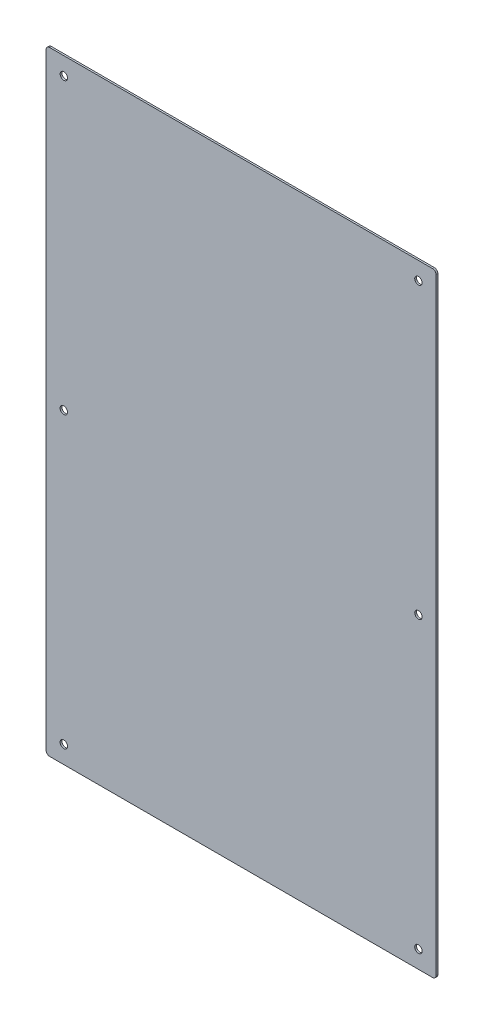
SolidWorks part; units mm, degrees
ref_plane "Спереди" through (0, 0, 0) normal (0, 0, 1) x (1, 0, 0)
ref_plane "Сверху" through (0, 0, 0) normal (0, 1, 0) x (1, 0, 0)
ref_plane "Справа" through (0, 0, 0) normal (1, 0, 0) x (0, 0, -1)
sketch "Эскиз1" plane through (0, 0, 0) normal (0, 0, 1) x (1, 0, 0)
  line L1 (0, -29.1001) -> (0, 23.6764) construction
  line L3 (-108.5, -174) -> (108.5, -174)
  line L4 (-110.5, -172) -> (-110.5, 172)
  line L5 (-108.5, 174) -> (108.5, 174)
  line L6 (110.5, -172) -> (110.5, 172)
  circle A0 centre (-100.5, 164) radius 2.1
  circle A1 centre (-100.5, 0) radius 2.1
  circle A2 centre (-100.5, -164) radius 2.1
  circle A3 centre (100.5, -164) radius 2.1
  circle A4 centre (100.5, 0) radius 2.1
  circle A5 centre (100.5, 164) radius 2.1
  arc A6 (-110.5, 172) -> (-108.5, 174) centre (-108.5, 172) cw
  arc A7 (108.5, 174) -> (110.5, 172) centre (108.5, 172) cw
  arc A8 (108.5, -174) -> (110.5, -172) centre (108.5, -172) ccw
  arc A9 (-108.5, -174) -> (-110.5, -172) centre (-108.5, -172) cw
  point P23 (-110.5, 174)
  point P26 (110.5, 174)
  point P29 (110.5, -174)
  point P32 (-110.5, -174)
  dimension "D3" = 4.2
  dimension "D5" = 10
  dimension "D6" = 4.2
  dimension "D7" = 10
  dimension "D8" = 2
  dimension "D9" = 328
  dimension "D10" = 164
  dimension "D1" = 348
  dimension "D2" = 221
  dimension "D4" = 10
extrude "Вытянуть1" add sketch "Эскиз1" along normal blind 1
